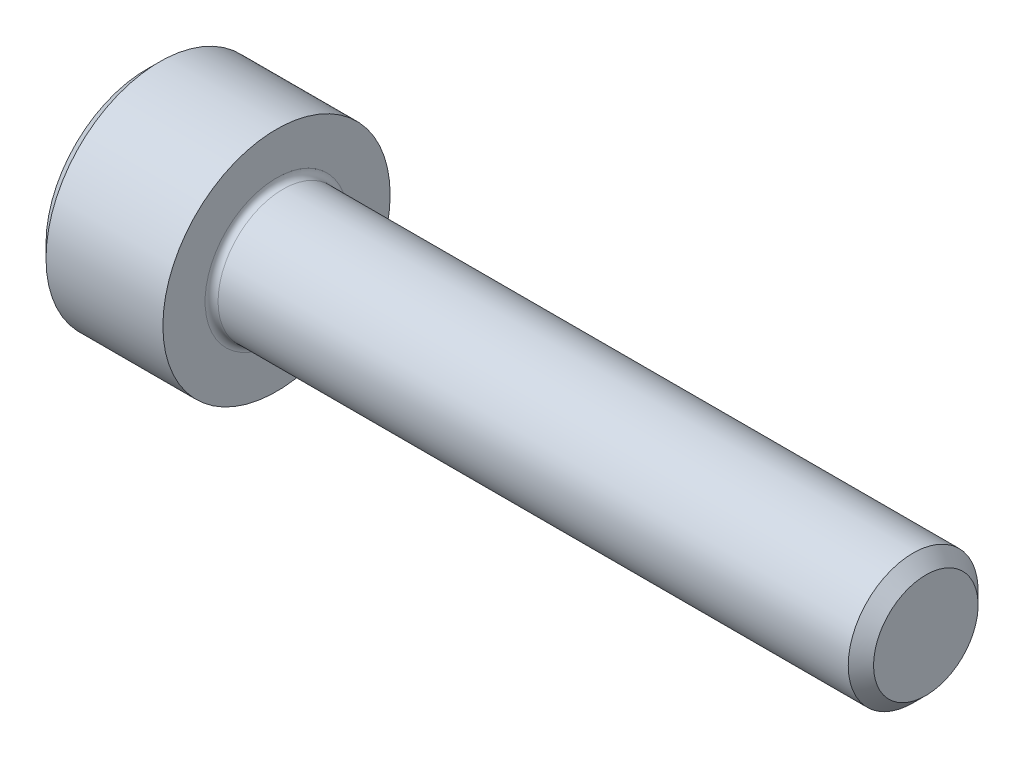
SolidWorks part; units mm, degrees
revolve "Base-Revolve" add sketch "BodySke"
sketch "BodySke" plane through (0, 0, 0) normal (0, 0, 1) x (1, 0, 0)
  line L0 (0, 0) -> (0, 3.1)
  line L1 (0.4, 3.5) -> (4, 3.5)
  line L2 (4, 3.5) -> (4, 2)
  line L3 (4, 2) -> (23.61, 2)
  line L4 (24, 1.61) -> (24, 0)
  line L5 (24, 0) -> (0, 0)
  line L6 (-31.75, 0) -> (127, 0) construction
  line L7 (0, 3.1) -> (0.4, 3.5)
  line L8 (24, 1.61) -> (23.61, 2)
  line L9 (0, -3.1) -> (0.4, -3.5) construction
  line L10 (24, -1.61) -> (23.61, -2) construction
  line L11 (4.7, 9.525) -> (4.7, 3.175) construction
  line L12 (4, 9.525) -> (4, 3.175) construction
  line L13 (-26, 9.525) -> (-26, 3.175) construction
  dimension "Diameter" = 4
  dimension "Head_ht" = 4
  dimension "Length" = 20
  dimension "Body_ch_ang" = 45
  dimension "Head_dia" = 7
  dimension "Head_ch_ang" = 45
  dimension "Minor_dia" = 3.22
  dimension "Advance" = 0.7
  dimension "Thread_nom" = 20
  dimension "Thread_length" = 50
  dimension "Head_ch_ht" = 0.4
cosmetic thread "ThreadCosmetic"
fillet "Fillet1" radius 0.2 1 edges at (4, 0, 2)
ref_plane "Plane1" through (0, 0, 0) normal (0, 0, 1) x (1, 0, 0)
ref_plane "Plane2" through (0, 0, 0) normal (0, 1, 0) x (1, 0, 0)
ref_plane "Plane3" through (0, 0, 0) normal (1, 0, 0) x (0, 0, -1)
sketch "Sketch2" plane through (0, 0, 0) normal (0, 0, 1) x (1, 0, 0)
  line L0 (0, 1.5355) -> (2, 1.5355)
  line L1 (2, 1.5355) -> (2.8865, 0)
  line L2 (-31.75, 0) -> (127, 0) construction
  line L3 (2.8865, 0) -> (0, 0)
  line L4 (0, 0) -> (0, 1.5355)
  line L5 (0, 3.1) -> (0, -3.1) construction
  line L6 (0, 0) -> (47.625, 0) construction
  line L7 (4, -3.5) -> (4, 3.5) construction
  dimension "D1" = 1.5355
  dimension "D2" = 60
revolve "Hex-PreBroach" cut sketch "Sketch2" angle 360 about L6
sketch "Sketch3" plane through (0, 0, 0) normal (-1, 0, 0) x (0, 0.5, 0.866)
  line L0 (0.8865, 1.5355) -> (-0.8865, 1.5355)
  line L1 (-0.8865, 1.5355) -> (-1.773, 0)
  line L2 (0.8865, 1.5355) -> (1.773, 0)
  line L3 (0.8865, -1.5355) -> (1.773, 0)
  line L4 (0.8865, -1.5355) -> (-0.8865, -1.5355)
  line L5 (-0.8865, -1.5355) -> (-1.773, 0)
  dimension "D1" = 1.5355
  dimension "D2" = 1.5355
  dimension "Hex_size" = 3.071
extrude "Hex" cut sketch "Sketch3" against normal blind 2
sketch "Sketch4" plane through (0, 0, 0) normal (-1, 0, 0) x (0, 0, 1)
  line L0 (0, 0) -> (1.7399, 0)
  line L1 (0, 0) -> (6.1484, 3.5498) construction
  line L2 (0, 0) -> (0.8699, 1.5068)
  line L3 (1.4457, 0.3947) -> (1.6607, 0.5189)
  line L4 (1.0647, 1.0546) -> (1.2797, 1.1788)
  arc A0 (1.4457, 0.3947) -> (1.0647, 1.0546) centre (0, 0) ccw
  arc A1 (1.7399, 0) -> (1.6607, 0.5189) centre (0, 0) ccw
  arc A2 (0.8699, 1.5068) -> (1.2797, 1.1788) centre (0, 0) cw
  dimension "D1" = 30
  dimension "D2" = 60
  dimension "Spline_p_dim" = 0.762
  dimension "D3" = 0.381
extrude "Spline" [suppressed] cut sketch "Sketch4" against normal blind 2
pattern_circular "CirPattern1" [suppressed] count 6 every 60
sketch "Sketch5" plane through (0, 0, 0) normal (0, 0, 1) x (1, 0, 0)
  line L0 (-31.75, 0) -> (127, 0) construction
  line L2 (0, 3.1) -> (0, -3.1) construction
  circle A0 centre (1.6, 0) radius 0.675
  dimension "Drilled_hole_dia" = 1.35
  dimension "Drilled_hole_loc" = 1.6
extrude "Hole" [suppressed] cut sketch "Sketch5" against normal through all and the other way through all
pattern_circular "Drilled-4" [suppressed] count 2 every 60
pattern_circular "Drilled-6" [suppressed] count 3 every 60
sketch "ThdSchSke" plane through (0, 0, 0) normal (0, 0, 1) x (1, 0, 0)
  line L0 (4.7, -1.61) -> (4.4269, -2)
  line L1 (4.7, -1.61) -> (4.9731, -2)
  line L2 (4.9731, -2) -> (4.9731, -2.5)
  line L3 (-3.175, 0) -> (5.1513, 0) construction
  line L5 (4.9731, -2.5) -> (4.4269, -2.5)
  line L6 (4.4269, -2.5) -> (4.4269, -2)
  line L7 (0, 3.1) -> (0, -3.1) construction
  dimension "Thread_minor" = 3.22
  dimension "Diameter" = 4
  dimension "Start" = 4.7
revolve "ThreadSchematic" [suppressed] cut sketch "ThdSchSke" angle 360 about L3
pattern_linear "ThdSchPat" [suppressed]
equation "\"D2@Sketch3\" = \"Hex_size@Sketch3\" / 2"
equation "\"D1@Sketch3\" = \"Hex_size@Sketch3\" / 2"
equation "\"D1@Sketch2\" = \"Hex_size@Sketch3\" / 2"
equation "\"D3@Sketch4\" = \"Spline_p_dim@Sketch4\" / 2"
equation "\"Thread_minor@ThreadCosmetic\"  =  \"Minor_dia@BodySke\""
equation "\"D2@CirPattern1\" = 360 / \"Num_teeth@CirPattern1\""
equation "\"Wall_thickness@Sketch2\" = \"Head_ht@BodySke\" - \"Key_eng@Hex\""
equation "\"Thread_length@ThreadCosmetic\" = ((sgn( (\"Length@BodySke\" - \"Advance@BodySke\" ) - \"Thread_nom@BodySke\" )-1)*( (\"Length@BodySke\" - \"Advance@BodySke\" ) - \"Thread_nom@BodySke\" ))/-2+ \"Thread_nom@BodySke\""
equation "\"Thread_minor@ThdSchSke\" = \"Minor_dia@BodySke\""
equation "\"Diameter@ThdSchSke\" = \"Diameter@BodySke\""
equation "\"Overcut@ThdSchSke\" = \"Diameter@BodySke\" * 1.25"
equation "\"Start@ThdSchSke\" = \"Head_ht@BodySke\" + \"Length@BodySke\" - \"Thread_length@ThreadCosmetic\"  '---Non-countersunk---"
equation "\"Num_threads@ThdSchPat\" = int( \"Thread_length@ThreadCosmetic\" / \"Advance@BodySke\" + 0.999 )  + 1"
equation "\"Advance@ThdSchPat\" = \"Thread_length@ThreadCosmetic\" /  (\"Num_threads@ThdSchPat\" - 1) 'relax it"
equation "\"Num_threads@ThdSchPat\" = \"Num_threads@ThdSchPat\" - sgn( \"Num_threads@ThdSchPat\" - 1) '---chamfered tips only---"
